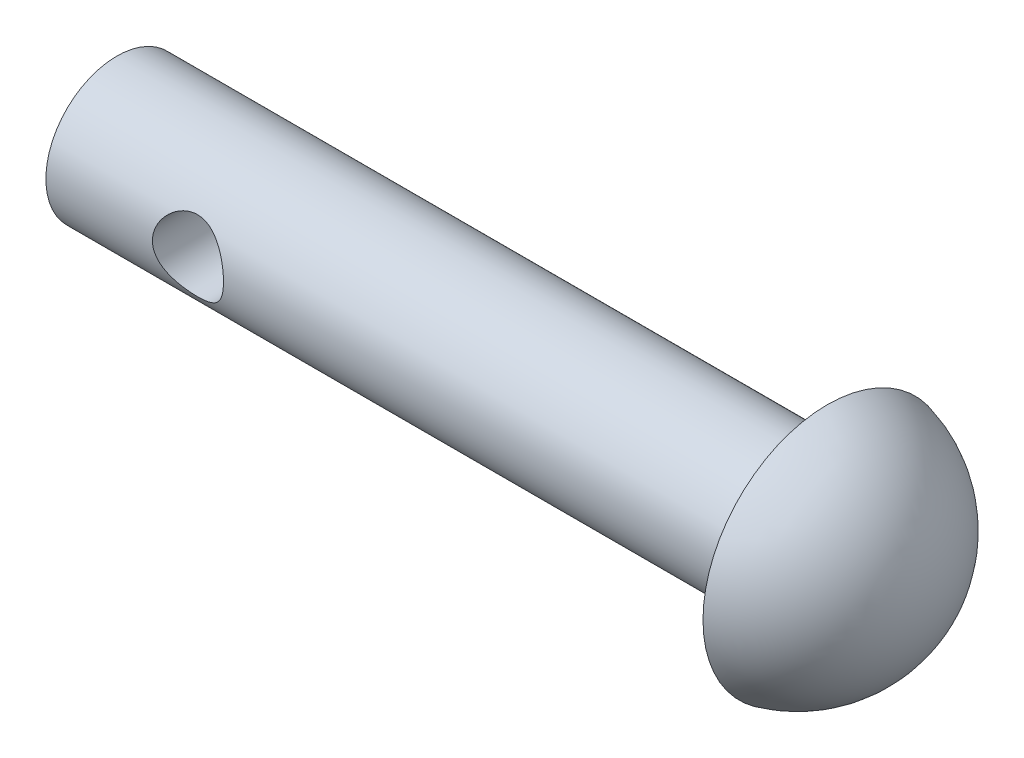
SolidWorks part; units mm, degrees
ref_plane "Front Plane" through (0, 0, 0) normal (0, 0, 1) x (1, 0, 0)
ref_plane "Top Plane" through (0, 0, 0) normal (0, 1, 0) x (1, 0, 0)
ref_plane "Right Plane" through (0, 0, 0) normal (1, 0, 0) x (0, 0, -1)
sketch "Sketch1" plane through (0, 0, 0) normal (1, 0, 0) x (0, 0, -1)
  circle A0 centre (0, 0) radius 2
  dimension "D1" = 4
extrude "Boss-Extrude1" add sketch "Sketch1" against normal blind 20
sketch "Sketch2" plane through (0, 0, 0) normal (0, 0, 1) x (1, 0, 0)
  line L0 (0, -2) -> (0, 2) construction
  circle A0 centre (-16, 0) radius 1
  dimension "D2" = 2
  dimension "D1" = 16
extrude "Cut-Extrude1" cut sketch "Sketch2" against normal through all and the other way through all
sketch "Sketch3" plane through (0, 0, 0) normal (0, 1, 0) x (1, 0, 0)
  line L0 (-7.5589, 0) -> (2.7574, 0) construction
  line L1 (2.7574, 0) -> (0, 0)
  line L2 (0, 0) -> (0, 3.5)
  arc A0 (0, 3.5) -> (2.7574, 0) centre (-0.8426, 0) cw
  dimension "D2" = 3.6
  dimension "D1" = 3.5
revolve "Revolve1" add sketch "Sketch3" angle 360 about L0
